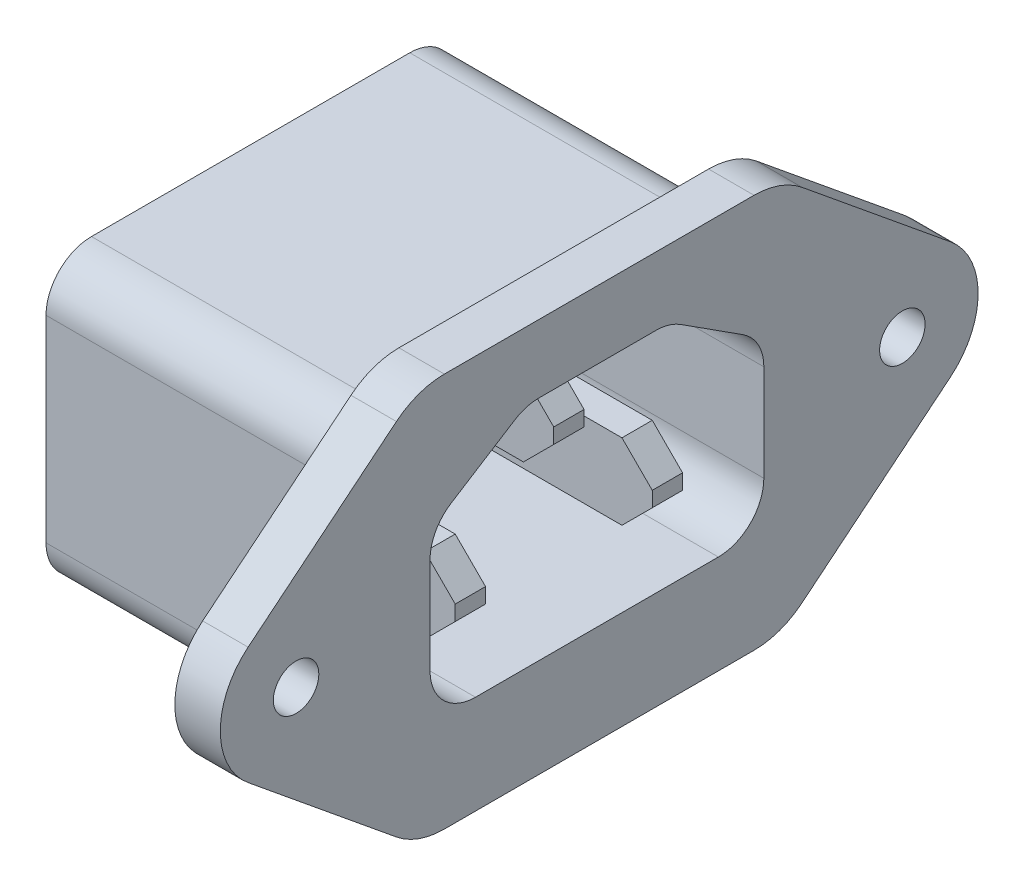
SolidWorks part; units mm, degrees
material "ABS"
ref_plane "Ground_Plane" through (0, 0, 0) normal (0, 0, 1) x (1, 0, 0)
ref_plane "VehicleCentre_Plane" through (0, 0, 0) normal (0, 1, 0) x (1, 0, 0)
ref_plane "FrontAxle_Plane" through (0, 0, 0) normal (1, 0, 0) x (0, 0, -1)
sketch "Sketch1" plane through (0, 0, 0) normal (1, 0, 0) x (0, 0, -1)
  line L0 (-23.165, 3.8708) -> (-13.381, 11.8708)
  line L1 (-10.2161, 13) -> (10.2161, 13)
  line L2 (13.381, 11.8708) -> (23.165, 3.8708)
  line L3 (-23.165, -3.8708) -> (-13.381, -11.8708)
  line L4 (-10.2161, -13) -> (10.2161, -13)
  line L5 (13.381, -11.8708) -> (23.165, -3.8708)
  arc A0 (-23.165, 3.8708) -> (-23.165, -3.8708) centre (-20, 0) ccw
  arc A1 (23.165, 3.8708) -> (23.165, -3.8708) centre (20, 0) cw
  circle A2 centre (-20, 0) radius 1.5
  circle A3 centre (20, 0) radius 1.5
  arc A4 (-13.381, -11.8708) -> (-10.2161, -13) centre (-10.2161, -8) ccw
  arc A5 (10.2161, -13) -> (13.381, -11.8708) centre (10.2161, -8) ccw
  arc A6 (10.2161, 13) -> (13.381, 11.8708) centre (10.2161, 8) cw
  arc A7 (-13.381, 11.8708) -> (-10.2161, 13) centre (-10.2161, 8) cw
  point P10 (0, 13)
  point P18 (12, -13)
  point P21 (12, 13)
  point P24 (-12, 13)
  dimension "D1" = 3
  dimension "D2" = 40
  dimension "D3" = 5
  dimension "D6" = 5
  dimension "D4" = 26
  dimension "D5" = 24
extrude "Boss-Extrude1" add sketch "Sketch1" along normal blind 3
sketch "Sketch2" plane through (0, 0, 0) normal (-1, 0, 0) x (0, 0, 1)
  line L1 (13.5, 9.5) -> (-13.5, 9.5)
  line L2 (13.5, 9.5) -> (13.5, -9.5)
  line L3 (13.5, -9.5) -> (-13.5, -9.5)
  line L4 (-13.5, 9.5) -> (-13.5, -9.5)
  line L5 (13.5, 9.5) -> (-13.5, -9.5) construction
  line L6 (13.5, -9.5) -> (-13.5, 9.5) construction
  point P0 (0, 0)
  dimension "D1" = 19
  dimension "D2" = 27
extrude "Boss-Extrude2" add sketch "Sketch2" along normal blind 20
fillet "Fillet1" radius 3 4 edges at (-10, -9.5, 13.5) (-10, 9.5, 13.5) (-10, -9.5, -13.5) (-10, 9.5, -13.5)
sketch "Sketch3" plane through (3, 0, 0) normal (1, 0, 0) x (0, 0, -1)
  line L0 (-3.9743, 8.5148) -> (3.7512, 8.5148)
  line L2 (-11.1629, 2.8656) -> (-11.1629, -3.4919)
  line L3 (-8.1629, -6.4919) -> (7.8608, -6.4919)
  line L4 (10.8608, 2.8782) -> (10.8608, -3.4919)
  line L5 (5.3712, 8.0398) -> (9.4808, 5.4032)
  line L6 (-5.5779, 8.0503) -> (-9.7665, 5.401)
  arc A0 (-11.1629, -3.4919) -> (-8.1629, -6.4919) centre (-8.1629, -3.4919) ccw
  arc A1 (7.8608, -6.4919) -> (10.8608, -3.4919) centre (7.8608, -3.4919) ccw
  arc A2 (10.8608, 2.8782) -> (9.4808, 5.4032) centre (7.8608, 2.8782) ccw
  arc A3 (3.7512, 8.5148) -> (5.3712, 8.0398) centre (3.7512, 5.5148) cw
  arc A4 (-3.9743, 8.5148) -> (-5.5779, 8.0503) centre (-3.9743, 5.5148) ccw
  arc A5 (-11.1629, 2.8656) -> (-9.7665, 5.401) centre (-8.1629, 2.8656) cw
  point P0 (0, 0)
  point P3 (-0.1115, 8.5148)
  point P14 (10.8608, 4.5179)
  point P22 (-11.1629, 4.5179)
  dimension "D1" = 3
  dimension "D2" = 3
extrude "Cut-Extrude1" cut sketch "Sketch3" against normal blind 16
sketch "Sketch4" plane through (-13, 0, 0) normal (1, 0, 0) x (0, 0, -1)
  line L0 (-6.5, -3) -> (6.5, -3) construction
  line L1 (1, 6.3698) -> (-1, 6.3698)
  line L2 (1, 6.3698) -> (1, 1.3698)
  line L3 (1, 1.3698) -> (-1, 1.3698)
  line L4 (-1, 6.3698) -> (-1, 1.3698)
  line L5 (1, 6.3698) -> (-1, 1.3698) construction
  line L6 (1, 1.3698) -> (-1, 6.3698) construction
  line L7 (-5.5, -0.5) -> (-7.5, -0.5)
  line L8 (-5.5, -0.5) -> (-5.5, -5.5)
  line L9 (-5.5, -5.5) -> (-7.5, -5.5)
  line L10 (-7.5, -0.5) -> (-7.5, -5.5)
  line L11 (-5.5, -0.5) -> (-7.5, -5.5) construction
  line L12 (-5.5, -5.5) -> (-7.5, -0.5) construction
  line L13 (7.5, -0.5) -> (5.5, -0.5)
  line L14 (7.5, -0.5) -> (7.5, -5.5)
  line L15 (7.5, -5.5) -> (5.5, -5.5)
  line L16 (5.5, -0.5) -> (5.5, -5.5)
  line L17 (7.5, -0.5) -> (5.5, -5.5) construction
  line L18 (7.5, -5.5) -> (5.5, -0.5) construction
  point P0 (0, 3.8698)
  point P5 (-6.5, -3)
  point P10 (6.5, -3)
  point P17 (0, -3)
  dimension "D1" = 13
  dimension "D2" = 6.8698
  dimension "D3" = 5
  dimension "D4" = 2
  dimension "D5" = 3
extrude "Boss-Extrude3" add sketch "Sketch4" along normal blind 14 separate body
chamfer "Chamfer1" distance 2 angle 45 2 edges at (1, 1.3698, 0) (1, 6.3698, 0)
chamfer "Chamfer2" distance 2 angle 45 2 edges at (1, -5.5, 6.5) (1, -0.5, 6.5)
chamfer "Chamfer3" distance 2 angle 45 2 edges at (1, -5.5, -6.5) (1, -0.5, -6.5)
